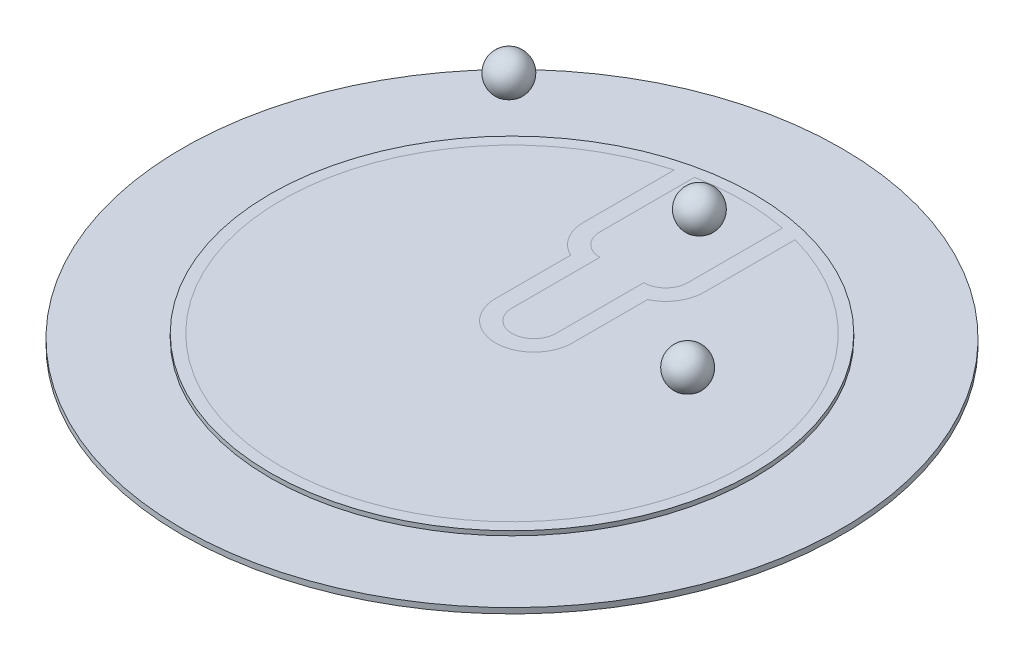
SolidWorks part; units mm, degrees
ref_plane "Front Plane" through (0, 0, 0) normal (0, 0, 1) x (1, 0, 0)
ref_plane "Top Plane" through (0, 0, 0) normal (0, 1, 0) x (1, 0, 0)
ref_plane "Right Plane" through (0, 0, 0) normal (1, 0, 0) x (0, 0, -1)
sketch "Sketch1" plane through (0, 0, 0) normal (0, 1, 0) x (1, 0, 0)
  circle A0 centre (0, 0) radius 15
  dimension "D1" = 30
extrude "Boss-Extrude1" add sketch "Sketch1" along normal blind 0.25
sketch "Sketch2" plane through (0, 0.25, 0) normal (0, 1, 0) x (1, 0, 0)
  circle A0 centre (0, 0) radius 11
  dimension "D1" = 22
extrude "Boss-Extrude2" add sketch "Sketch2" along normal blind 0.2
sketch "Sketch3" plane through (0, 0.45, 0) normal (0, 1, 0) x (1, 0, 0)
  line L0 (-2, 10.3078) -> (-2, 6)
  line L1 (0, 0) -> (2.0523, 0) construction
  line L2 (0, 0) -> (0, 15) construction
  line L3 (-1, 5) -> (-1, 1)
  line L4 (-2.75, 10.1335) -> (-2.75, 6)
  line L5 (-1.75, 4.4189) -> (-1.75, 1)
  line L6 (2.75, 10.1335) -> (2.75, 6)
  line L7 (1.75, 4.4189) -> (1.75, 1)
  line L8 (1, 5) -> (1, 1)
  line L9 (2, 10.3078) -> (2, 6)
  line L11 (-2.75, 10.3078) -> (-2.75, 6) construction
  arc A0 (-2.75, 10.1335) -> (2.75, 10.1335) centre (0, 0) ccw
  circle A1 centre (0, 0) radius 15 construction
  arc A2 (-1, 1) -> (0, 0) centre (0, 1) ccw
  arc A3 (-2, 6) -> (-1, 5) centre (-1, 6) ccw
  arc A4 (-2.75, 6) -> (-1.75, 4.4189) centre (-1, 6) ccw
  arc A5 (-1.75, 1) -> (0, -0.75) centre (0, 1) ccw
  arc A6 (2.75, 6) -> (1.75, 4.4189) centre (1, 6) cw
  arc A7 (1.75, 1) -> (0, -0.75) centre (0, 1) cw
  arc A8 (1, 1) -> (0, 0) centre (0, 1) cw
  arc A9 (2, 6) -> (1, 5) centre (1, 6) cw
  arc A10 (2, 10.3078) -> (-2, 10.3078) centre (0, 0) ccw
  circle A11 centre (0, 0) radius 11 construction
  circle A12 centre (0, 0) radius 11
  dimension "D1" = 21
  dimension "D4" = 5
  dimension "D2" = 2
  dimension "D3" = 1
  dimension "D5" = 6
  dimension "D6" = 0.75
split line "Split Line1"
sketch "Sketch4" plane through (0, 0.45, 0) normal (0, 1, 0) x (1, 0, 0)
  line L0 (-9.9058, 9.7621) -> (-8.1463, 8.2898) construction
  point P1 (0, 8.529)
  point P2 (5.9703, 2.0248)
  point P3 (-9.9058, 9.7621)
sketch "Sketch5" plane through (0, 0, 0) normal (1, 0, 0) x (0, 0, -1)
  line L0 (8.529, 0.45) -> (8.529, 1.95) construction
  line L1 (8.529, 0.45) -> (9.129, 0.45)
  line L2 (11, 0.45) -> (-11, 0.45) construction
  line L3 (8.3447, 1.95) -> (8.529, 1.95) construction
  line L4 (6, 0.45) -> (10.1335, 0.45) construction
  line L5 (9.129, 0.45) -> (9.129, -0.5744) construction
  line L6 (8.529, 1.95) -> (8.529, 0.45)
  arc A0 (9.129, 0.45) -> (8.529, 1.95) centre (8.529, 1.08) ccw
  dimension "D1" = 1.5
  dimension "D2" = 0.6
revolve "Revolve1" add sketch "Sketch5" angle 360 about L6
move or copy body "Body-Move/Copy2" bodies to move or copy 104 copy yes number of copies 1 translate (5.9703, 0, 6.5042)
ref_plane "Plane1" through (0.7252, 0, -0.8667) normal (-0.6417, 0, 0.7669) x (0.7669, 0, 0.6417)
sketch "Sketch7" plane through (0.7252, 0, -0.8667) normal (-0.6417, 0, 0.7669) x (0.7669, 0, 0.6417)
  line L0 (-13.8617, 0.45) -> (-13.8617, 1.557) construction
  line L1 (-13.8617, 0.25) -> (-13.2617, 0.25)
  line L2 (-13.8617, 1.75) -> (-13.8617, 0.25)
  line L3 (15, 0.25) -> (-15, 0.25) construction
  arc A0 (-13.2617, 0.25) -> (-13.8617, 1.75) centre (-13.8617, 0.88) ccw
  dimension "D3" = 0.87
  dimension "D1" = 0.6
  dimension "D2" = 1.5
revolve "Revolve2" add sketch "Sketch7" angle 360 about L0
